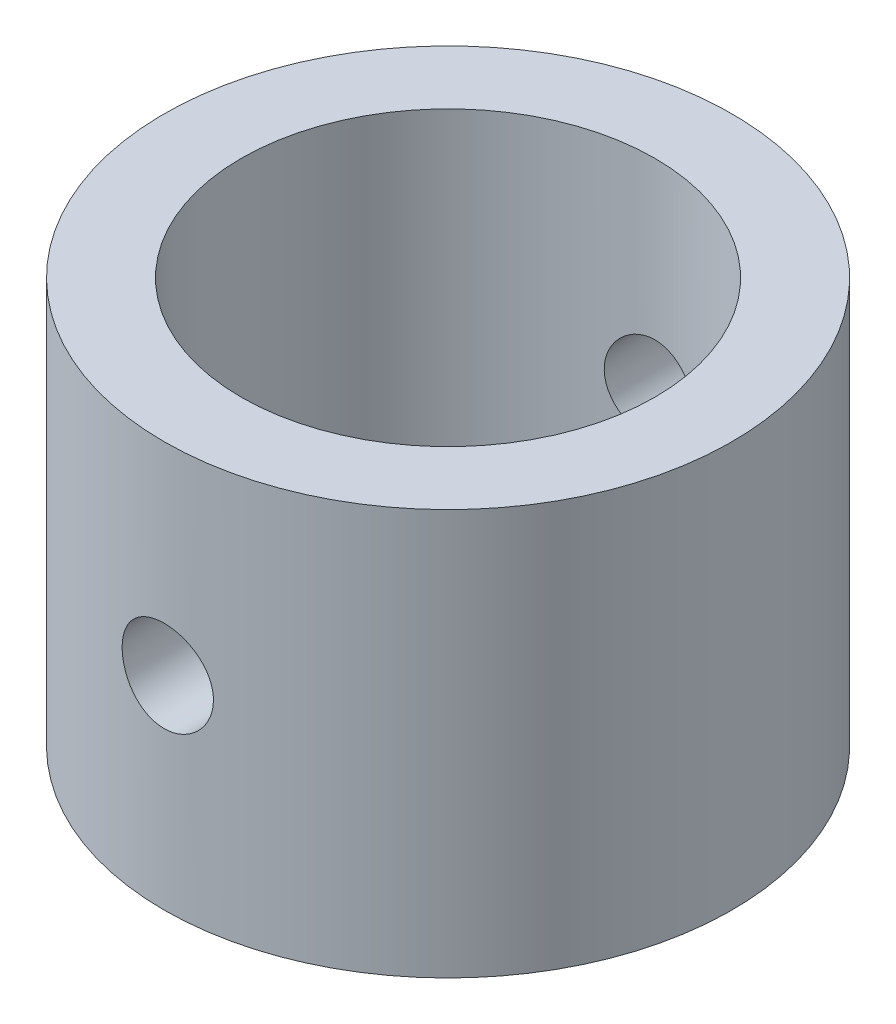
SolidWorks part; units mm, degrees
ref_plane "Спереди" through (0, 0, 0) normal (0, 0, 1) x (1, 0, 0)
ref_plane "Сверху" through (0, 0, 0) normal (0, 1, 0) x (1, 0, 0)
ref_plane "Справа" through (0, 0, 0) normal (1, 0, 0) x (0, 0, -1)
sketch "Эскиз1" plane through (0, 0, 0) normal (0, 1, 0) x (1, 0, 0)
  circle A0 centre (0, 0) radius 10.2
  circle A1 centre (0, 0) radius 14
  dimension "D1" = 20.4
  dimension "D2" = 28
extrude "Бобышка-Вытянуть1" add sketch "Эскиз1" along normal mid plane 20
sketch "Эскиз3" plane through (0, 0, 0) normal (0, 0, 1) x (1, 0, 0)
  circle A0 centre (0, 0) radius 2.25
  dimension "D1" = 4.5
extrude "Вырез-Вытянуть1" cut sketch "Эскиз3" against normal through all both and the other way through all
equation "\"big_bearing_d1\"= 19.9"
equation "\"big_bearing_d2\"= 42"
equation "\"big_bearing_h\"= 11.9"
equation "\"print_offset\"= 0.5"
equation "\"small_bearing_d1\"= 2.9"
equation "\"small_bearing_d2\"= 10"
equation "\"small_bearing_h\"= 4"
equation "\"tube_d\"= 16"
equation "\"small_bearing_distance\"= 2"
equation "\"D1@Эскиз1\"=\"big_bearing_d1\"+\"print_offset\""
